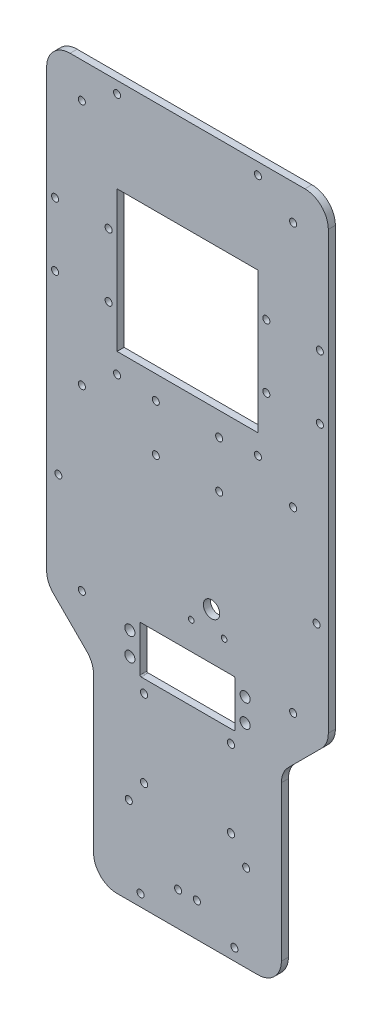
SolidWorks part; units mm, degrees
ref_plane "Alzado" through (0, 0, 0) normal (0, 0, 1) x (1, 0, 0)
ref_plane "Planta" through (0, 0, 0) normal (0, 1, 0) x (1, 0, 0)
ref_plane "Vista lateral" through (0, 0, 0) normal (1, 0, 0) x (0, 0, -1)
sketch "Croquis8" plane through (0, 0, 0) normal (0, 0, 1) x (1, 0, 0)
  line L17 (-30, -150) -> (30, -150)
  line L18 (40, -140) -> (40, -74.1421)
  line L19 (-40, -74.1421) -> (-40, -140)
  line L20 (42.9289, -67.0711) -> (57.0711, -52.9289)
  line L28 (-57.0711, -52.9289) -> (-42.9289, -67.0711)
  line L29 (60, -45.8579) -> (60, 140)
  line L30 (50, 150) -> (-50, 150)
  line L31 (-60, 140) -> (-60, -45.8579)
  line L36 (-30, 50) -> (30, 50)
  line L37 (-30, 110) -> (-30, 50)
  line L38 (30, 110) -> (-30, 110)
  line L39 (30, 50) -> (30, 110)
  circle A12 centre (33.6, 66.5) radius 1.5
  circle A13 centre (56.4, 66.5) radius 1.5
  circle A14 centre (56.4, 93.5) radius 1.5
  circle A15 centre (33.6, 93.5) radius 1.5
  circle A16 centre (13.5, 40) radius 1.5
  circle A17 centre (13.5, 20) radius 1.5
  circle A18 centre (-13.5, 20) radius 1.5
  circle A19 centre (-13.5, 40) radius 1.5
  circle A20 centre (-56.4, 66.5) radius 1.5
  circle A21 centre (-33.6, 66.5) radius 1.5
  circle A22 centre (-33.6, 93.5) radius 1.5
  circle A23 centre (-56.4, 93.5) radius 1.5
  arc A53 (30, -150) -> (40, -140) centre (30, -140) ccw
  arc A54 (-40, -140) -> (-30, -150) centre (-30, -140) ccw
  arc A55 (-40, -74.1421) -> (-42.9289, -67.0711) centre (-50, -74.1421) ccw
  arc A56 (57.0711, -52.9289) -> (60, -45.8579) centre (50, -45.8579) ccw
  arc A57 (42.9289, -67.0711) -> (40, -74.1421) centre (50, -74.1421) ccw
  arc A67 (-60, -45.8579) -> (-57.0711, -52.9289) centre (-50, -45.8579) ccw
  arc A68 (60, 140) -> (50, 150) centre (50, 140) ccw
  arc A69 (-50, 150) -> (-60, 140) centre (-50, 140) ccw
  dimension "D1" = 3
  dimension "D2" = 3
  dimension "D5" = 10
  dimension "D6" = 10
  dimension "D8" = 10
  dimension "D9" = 10
  dimension "D10" = 10
  dimension "D11" = 10
  dimension "D15" = 10
  dimension "D16" = 10
  dimension "D3" = 100
  dimension "D4" = 185.8579
  dimension "D7" = 185.8579
  dimension "D12" = 65.8579
  dimension "D13" = 65.8579
  dimension "D14" = 60
  dimension "D17" = 14.1421
  dimension "D18" = 14.1421
  dimension "D19" = 80
  dimension "D20" = 120
  dimension "D21" = 60
  dimension "D22" = 60
  dimension "D23" = 60
  dimension "D24" = 3.6
  dimension "D25" = 22.8
  dimension "D26" = 27
  dimension "D27" = 30
  dimension "D28" = 10
  dimension "D29" = 46.5
extrude "Saliente-Extruir1" add sketch "Croquis8" along normal blind 3
sketch "Croquis14" plane through (0, 0, 0) normal (0, 0, -1) x (-1, 0, 0)
  line L0 (0, -150) -> (0, 150) construction
  line L1 (30, -150) -> (-30, -150) construction
  line L2 (-50, 150) -> (50, 150) construction
  line L3 (60, 0) -> (-60, 0) construction
  line L4 (-60, -45.8579) -> (-60, 140) construction
  line L5 (13.5, 20) -> (13.5, 40) construction
  line L6 (60, -45.8579) -> (-60, -45.8579) construction
  line L7 (13.5, 30) -> (60, 30) construction
  line L8 (60, 140) -> (60, -45.8579) construction
  circle A0 centre (45, 135) radius 1.5
  circle A1 centre (-45, 135) radius 1.5
  circle A2 centre (-45, -45.8579) radius 1.5
  circle A3 centre (45, -45.8579) radius 1.5
  circle A4 centre (45, 30) radius 1.5
  circle A5 centre (-45, 30) radius 1.5
  point P12 (0, 0)
  dimension "D1" = 3
  dimension "D2" = 15
  dimension "D3" = 3
  dimension "D5" = 3
  dimension "D4" = 15
extrude "Cortar-Extruir5" cut sketch "Croquis14" against normal through all
sketch "Croquis15" plane through (0, 0, 0) normal (0, 0, -1) x (-1, 0, 0)
  line L0 (40, -140) -> (0, -140) construction
  line L1 (60, 140) -> (0, 140) construction
  line L2 (0, 150) -> (0, 110) construction
  line L3 (-50, 150) -> (50, 150) construction
  line L4 (-30, 110) -> (30, 110) construction
  line L5 (0, 140) -> (-60, 140) construction
  line L6 (-30, 140) -> (-30, 150) construction
  line L7 (30, 140) -> (30, 150) construction
  line L8 (0, -140) -> (0, -150) construction
  line L9 (30, -150) -> (-30, -150) construction
  line L10 (40, -74.1421) -> (40, -140) construction
  line L11 (0, -140) -> (-40, -140) construction
  line L12 (20, -140) -> (20, -150) construction
  line L13 (45, -45.8579) -> (45, 30) construction
  line L14 (45, -7.9289) -> (60, -7.9289) construction
  line L15 (60, 140) -> (60, -45.8579) construction
  circle A1 centre (30, 145) radius 1.5
  circle A2 centre (-30, 145) radius 1.5
  arc A3 (30, -150) -> (40, -140) centre (30, -140) ccw construction
  circle A4 centre (20, -145) radius 1.5
  circle A5 centre (-20, -145) radius 1.5
  circle A6 centre (55, -7.9289) radius 1.5
  circle A7 centre (-55, -7.9289) radius 1.5
  dimension "D1" = 3
  dimension "D2" = 3
  dimension "D3" = 3
  dimension "D4" = 5
extrude "Cortar-Extruir6" cut sketch "Croquis15" against normal through all
sketch "Croquis16" plane through (0, 0, 3) normal (0, 0, 1) x (1, 0, 0)
  line L3 (20.25, -55.5) -> (20.25, -54.5)
  line L5 (20.25, -54.5) -> (20.25, -45.5)
  line L10 (-19.75, -65) -> (19.75, -65) construction
  line L11 (-20.25, -45.5) -> (-20.25, -64.5) construction
  line L12 (19.75, -45) -> (-19.75, -45) construction
  line L13 (20.25, -64.5) -> (20.25, -45.5) construction
  line L22 (-20.25, -55.5) -> (-20.25, -54.5)
  line L24 (-19.75, -65) -> (19.75, -65)
  line L25 (-20.25, -45.5) -> (-20.25, -54.5)
  line L26 (19.75, -45) -> (-19.75, -45)
  line L27 (20.25, -64.5) -> (20.25, -55.5)
  line L28 (-20.25, -55.5) -> (-20.25, -64.5)
  arc A0 (-20.25, -64.5) -> (-19.75, -65) centre (-19.75, -64.5) ccw construction
  arc A1 (20.25, -45.5) -> (19.75, -45) centre (19.75, -45.5) ccw construction
  arc A2 (-19.75, -45) -> (-20.25, -45.5) centre (-19.75, -45.5) ccw construction
  arc A3 (19.75, -65) -> (20.25, -64.5) centre (19.75, -64.5) ccw construction
  arc A4 (-20.25, -64.5) -> (-19.75, -65) centre (-19.75, -64.5) ccw
  arc A5 (20.25, -45.5) -> (19.75, -45) centre (19.75, -45.5) ccw
  arc A6 (-19.75, -45) -> (-20.25, -45.5) centre (-19.75, -45.5) ccw
  arc A7 (19.75, -65) -> (20.25, -64.5) centre (19.75, -64.5) ccw
extrude "Cortar-Extruir7" cut sketch "Croquis16" against normal blind 23
sketch "Croquis17" plane through (0, 0, 0) normal (0, 0, -1) x (-1, 0, 0)
  arc A0 (-6.75, -25) -> (-13.75, -25) centre (-10.25, -25) ccw construction
  arc A1 (-13.75, -25) -> (-6.75, -25) centre (-10.25, -25) ccw construction
  circle A2 centre (-25, -113) radius 1.5 construction
  circle A3 centre (25, -113) radius 1.5 construction
  circle A4 centre (-18.5, -70.5) radius 1.55 construction
  circle A5 centre (18.5, -70.5) radius 1.55 construction
  circle A6 centre (-18.5, -103.5) radius 1.55 construction
  circle A7 centre (18.5, -103.5) radius 1.55 construction
  arc A8 (-6.75, -25) -> (-13.75, -25) centre (-10.25, -25) ccw
  arc A9 (-13.75, -25) -> (-6.75, -25) centre (-10.25, -25) ccw
  circle A10 centre (-25, -113) radius 1.5
  circle A11 centre (25, -113) radius 1.5
  circle A12 centre (-18.5, -70.5) radius 1.55
  circle A13 centre (18.5, -70.5) radius 1.55
  circle A14 centre (-18.5, -103.5) radius 1.55
  circle A15 centre (18.5, -103.5) radius 1.55
extrude "Cortar-Extruir8" cut sketch "Croquis17" against normal blind 10
sketch "Croquis18" plane through (0, 0, 3) normal (0, 0, 1) x (1, 0, 0)
  circle A0 centre (1.6, -33.2) radius 1.2 construction
  circle A1 centre (15.6, -33.2) radius 1.2 construction
  circle A2 centre (1.6, -33.2) radius 1.2
  circle A3 centre (15.6, -33.2) radius 1.2
extrude "Cortar-Extruir9" cut sketch "Croquis18" against normal blind 10
sketch "Croquis19" plane through (0, 0, 3) normal (0, 0, 1) x (1, 0, 0)
  circle A4 centre (-4, -135.5499) radius 1.5
  circle A5 centre (4, -135.5499) radius 1.5
  dimension "D1" = 3
  dimension "D2" = 3
extrude "Cortar-Extruir10" cut sketch "Croquis19" against normal blind 10
sketch "Croquis20" plane through (0, 0, 3) normal (0, 0, 1) x (1, 0, 0)
  line L0 (60, -45.8579) -> (60, 140) construction
  line L1 (-60, 140) -> (-60, -45.8579) construction
  line L2 (-30, 50) -> (30, 50) construction
  circle A0 centre (-30, 41.5) radius 1.5
  circle A1 centre (30, 41.5) radius 1.5
  dimension "D1" = 3
  dimension "D2" = 3
  dimension "D3" = 30
  dimension "D4" = 30
  dimension "D5" = 8.5
extrude "Cortar-Extruir11" cut sketch "Croquis20" against normal blind 10
sketch "Croquis22" plane through (0, 0, 3) normal (0, 0, 1) x (1, 0, 0)
  arc A0 (26.3122, -48.9182) -> (26.3122, -51.3818) centre (24.55, -50.15) ccw construction
  arc A1 (26.3122, -58.6182) -> (26.3122, -61.0818) centre (24.55, -59.85) ccw construction
  arc A2 (-26.3122, -61.0818) -> (-26.3122, -58.6182) centre (-24.55, -59.85) ccw construction
  arc A3 (-26.3122, -51.3818) -> (-26.3122, -48.9182) centre (-24.55, -50.15) ccw construction
  arc A4 (26.3122, -48.9182) -> (26.3122, -51.3818) centre (24.55, -50.15) ccw
  arc A5 (26.3122, -58.6182) -> (26.3122, -61.0818) centre (24.55, -59.85) ccw
  arc A6 (-26.3122, -61.0818) -> (-26.3122, -58.6182) centre (-24.55, -59.85) ccw
  arc A7 (-26.3122, -51.3818) -> (-26.3122, -48.9182) centre (-24.55, -50.15) ccw
  arc A8 (26.3122, -51.3818) -> (26.3122, -48.9182) centre (24.55, -50.15) ccw
  arc A9 (26.3122, -61.0818) -> (26.3122, -58.6182) centre (24.55, -59.85) ccw
  arc A10 (-26.3122, -61.0818) -> (-26.3122, -58.6182) centre (-24.55, -59.85) cw
  arc A11 (-26.3122, -51.3818) -> (-26.3122, -48.9182) centre (-24.55, -50.15) cw
extrude "Cortar-Extruir12" cut sketch "Croquis22" against normal blind 10
